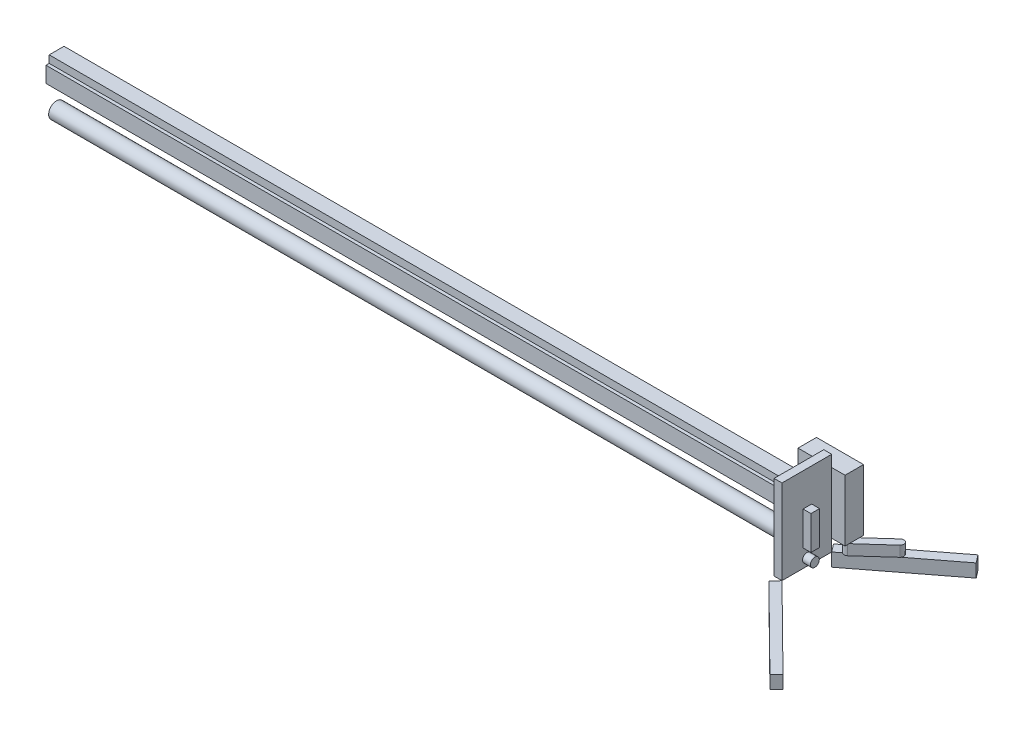
SolidWorks part; units mm, degrees
ref_plane "Front Plane" through (0, 0, 0) normal (0, 0, 1) x (1, 0, 0)
ref_plane "Top Plane" through (0, 0, 0) normal (0, 1, 0) x (1, 0, 0)
ref_plane "Right Plane" through (0, 0, 0) normal (1, 0, 0) x (0, 0, -1)
sketch "Sketch2" plane through (0, 0, 0) normal (-1, 0, 0) x (0, 0, 1)
  line L3 (-19.8706, 17.881) -> (-11.8706, 17.881)
  line L4 (-11.8706, 23.881) -> (-11.8706, 17.881)
  line L9 (-19.8706, 17.881) -> (-19.8706, 23.881)
  line L10 (-19.8706, 23.881) -> (-18.7033, 23.881)
  line L11 (-18.7033, 23.881) -> (-18.7033, 26.685)
  line L13 (-13.0867, 26.685) -> (-13.0867, 23.881)
  line L14 (-13.0867, 23.881) -> (-11.8706, 23.881)
  line L16 (-18.7033, 26.685) -> (-13.0867, 26.685)
  circle A0 centre (-15.8706, 7.1987) radius 3
  dimension "D1" = 6
  dimension "D2" = 8
extrude "Boss-Extrude1" add sketch "Sketch2" against normal blind 282
sketch "Sketch3" plane through (282, 0, 0) normal (1, 0, 0) x (0, 0, -1)
  line L1 (6.0161, 32.098) -> (24.8682, 32.098)
  line L2 (6.0161, 32.098) -> (6.0161, 0)
  line L3 (6.0161, 0) -> (24.8682, 0)
  line L4 (24.8682, 32.098) -> (24.8682, 0)
extrude "Boss-Extrude2" add sketch "Sketch3" along normal blind 3
sketch "Sketch4" plane through (0, 0, 0) normal (0, -1, 0) x (1, 0, 0)
  line L1 (285, -24.8682) -> (315.9936, -48.672)
  line L2 (315.9936, -48.672) -> (313.6963, -51.663)
  line L3 (313.6963, -51.663) -> (282.7028, -27.8592)
  line L6 (285, -6.0161) -> (315.9936, 24.5946)
  line L7 (315.9936, 24.5946) -> (313.5285, 27.0906)
  line L8 (313.5285, 27.0906) -> (282.7028, -3.3543)
  line L10 (282.7028, -3.3543) -> (285, -6.0161)
  line L11 (285, -24.8682) -> (282.7028, -27.8592)
extrude "Boss-Extrude3" add sketch "Sketch4" along normal blind 5 separate body
sketch "Sketch5" plane through (0, 0, -24.8682) normal (0, 0, -1) x (-1, 0, 0)
  line L1 (-290.0706, 27.7483) -> (-272.2342, 27.7483)
  line L2 (-290.0706, 27.7483) -> (-290.0706, 4.4881)
  line L3 (-290.0706, 4.4881) -> (-272.2342, 4.4881)
  line L4 (-272.2342, 27.7483) -> (-272.2342, 4.4881)
extrude "Boss-Extrude4" add sketch "Sketch5" along normal blind 7
sketch "Sketch6" plane through (0, 4.4881, 0) normal (0, -1, 0) x (1, 0, 0)
  line L0 (288.7866, -27.2256) -> (299.1833, -36.6076) construction
  line L1 (289.7555, -26.152) -> (300.1522, -35.534)
  line L2 (287.8177, -28.2993) -> (298.2144, -37.6813)
  arc A0 (289.7555, -26.152) -> (287.8177, -28.2993) centre (288.7866, -27.2256) ccw
  arc A1 (298.2144, -37.6813) -> (300.1522, -35.534) centre (299.1833, -36.6076) ccw
  point P2 (293.9849, -31.9166)
extrude "Boss-Extrude5" add sketch "Sketch6" along normal blind 4
sketch "Sketch7" plane through (285, 0, 0) normal (1, 0, 0) x (0, 0, -1)
  line L6 (14.0043, 19.5486) -> (17.2679, 19.5486)
  line L7 (14.0043, 19.5486) -> (14.0043, 6.7547)
  line L8 (14.0043, 6.7547) -> (17.2679, 6.7547)
  line L9 (17.2679, 19.5486) -> (17.2679, 6.7547)
  circle A0 centre (15.4804, 2.8231) radius 1.6789
extrude "Boss-Extrude6" add sketch "Sketch7" along normal blind 3
